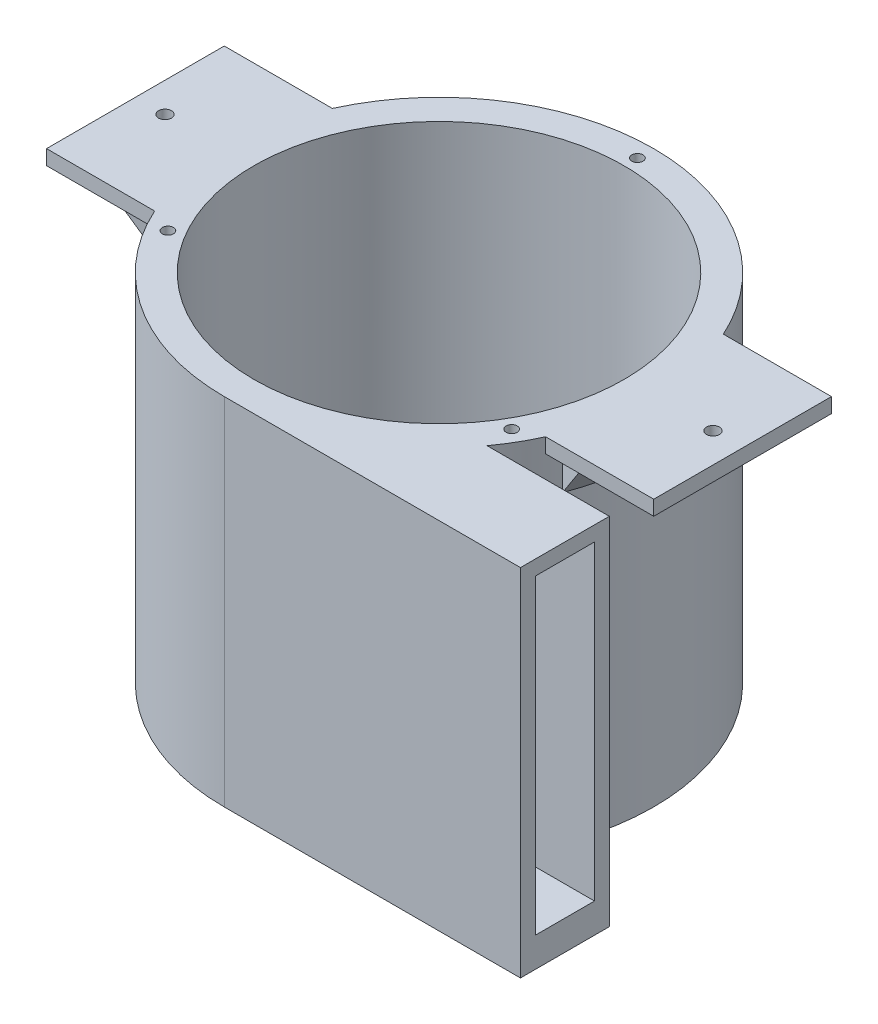
SolidWorks part; units mm, degrees
material "PET"
ref_plane "Front Plane" through (0, 0, 0) normal (0, 0, 1) x (1, 0, 0)
ref_plane "Top Plane" through (0, 0, 0) normal (0, 1, 0) x (1, 0, 0)
ref_plane "Right Plane" through (0, 0, 0) normal (1, 0, 0) x (0, 0, -1)
sketch "Sketch1" plane through (0, 0, 0) normal (0, 1, 0) x (1, 0, 0)
  line L0 (286.7619, 0) -> (-286.7619, 0) construction
  line L1 (0, -187.8106) -> (0, 187.8106) construction
  circle A0 centre (0, 0) radius 90.17 construction
  circle A2 centre (0, 0) radius 92.075
  circle A3 centre (0, 0) radius 79.375
  point P6 (0, 0)
  point P9 (0, 0)
  dimension "D1" = 180.34
  dimension "D3" = 184.15
  dimension "D2" = 12.7
extrude "Boss-Extrude1" add sketch "Sketch1" along normal mid plane 139.7
sketch "Sketch2" plane through (0, -69.85, 0) normal (0, -1, 0) x (1, 0, 0)
  circle A0 centre (0, 0) radius 92.075
extrude "Boss-Extrude2" add sketch "Sketch2" along normal blind 12.7
sketch "Sketch3" plane through (0, -82.55, 0) normal (0, -1, 0) x (1, 0, 0)
  circle A0 centre (0, 0) radius 8.7312
  dimension "D1" = 17.4625
extrude "Cut-Extrude1" cut sketch "Sketch3" against normal blind 12.7
sketch "Sketch4" plane through (0, 69.85, 0) normal (0, 1, 0) x (1, 0, 0)
  line L0 (-164.275, 0) -> (164.275, 0) construction
  line L1 (0, -105.3547) -> (0, 105.3547) construction
  circle A0 centre (0, 0) radius 85.09 construction
  circle A1 centre (0, 85.09) radius 2.3812
  circle A2 centre (73.6901, -42.545) radius 2.3813
  circle A3 centre (-73.6901, -42.545) radius 2.3813
  point P5 (0, 0)
  point P9 (0, 0)
  point P19 (0, 0)
  dimension "D1" = 170.18
  dimension "D2" = 4.7625
  dimension "D3" = 3
extrude "Cut-Extrude2" cut sketch "Sketch4" against normal blind 19.05
sketch "Sketch6" plane through (0, -82.55, 0) normal (0, -1, 0) x (1, 0, 0)
  line L0 (-180.9489, 0) -> (180.9489, 0) construction
  line L1 (0, -132.0673) -> (0, 132.0673) construction
  line L2 (0, 92.075) -> (127, 92.075)
  line L3 (127, 92.075) -> (127, 53.975)
  line L4 (127, 53.975) -> (74.5956, 53.975)
  circle A0 centre (0, 0) radius 92.075 construction
  arc A1 (74.5956, 53.975) -> (0, 92.075) centre (0, 0) ccw
  point P5 (0, 0)
  point P9 (0, 0)
  circle M4 centre (0, 0) radius 92.075
extrude "Boss-Extrude3" add sketch "Sketch6" against normal blind 12.7 contours L4 L3 L2 M4
sketch "Sketch7" plane through (0, 69.85, 0) normal (0, 1, 0) x (1, 0, 0)
  line L0 (0, 133.8457) -> (0, -133.8457) construction
  line L1 (127.6612, 0) -> (-127.6612, 0) construction
  line L2 (0, -92.075) -> (127, -92.075)
  line L3 (0, -92.075) -> (127, -92.075) construction
  line L4 (127, -92.075) -> (127, -53.975)
  line L5 (127, -92.075) -> (127, -53.975) construction
  line L6 (127, -53.975) -> (0, -53.975)
  line L8 (0, -53.975) -> (0, -92.075)
  arc A0 (0, -92.075) -> (74.5956, -53.975) centre (0, 0) ccw construction
  circle A2 centre (0, 0) radius 92.075 construction
  point P5 (0, 0)
  point P9 (0, 0)
  circle M4 centre (0, 0) radius 92.075
  circle M5 centre (0, 0) radius 79.375
extrude "Cut-Extrude4" cut sketch "Sketch7" against normal blind 139.7 contours L4 L6 L2 M4 | L8 L6 M5 M4 | L6 L8 M5
sketch "Sketch8" plane through (0, -69.85, 0) normal (0, 1, 0) x (1, 0, 0)
  line L0 (0, -92.075) -> (127, -92.075)
  line L1 (0, -92.075) -> (127, -92.075) construction
  line L2 (127, -92.075) -> (127, -85.725)
  line L3 (127, -92.075) -> (127, -53.975) construction
  line L6 (0, -79.375) -> (0, -92.075) construction
  line L7 (0, -79.375) -> (0, -92.075) construction
  line L8 (127, -85.725) -> (0, -85.725)
  line L9 (0, -85.725) -> (0, -92.075)
  arc A2 (74.5956, -53.975) -> (0, -92.075) centre (0, 0) ccw construction
  line M4 (0, -79.375) -> (0, -92.075)
  line M5 (0, -92.075) -> (127, -92.075)
  line M6 (127, -92.075) -> (127, -53.975)
extrude "Boss-Extrude4" add sketch "Sketch8" along normal blind 139.7 contours L8 M6 M4 M5
sketch "Sketch9" plane through (0, -69.85, 0) normal (0, 1, 0) x (1, 0, 0)
  line L0 (-187.5492, 0) -> (187.5492, 0) construction
  line L1 (0, 118.5749) -> (0, -118.5749) construction
  line L2 (127, -53.975) -> (58.1987, -53.975)
  line L3 (74.5956, -53.975) -> (58.1987, -53.975) construction
  line L4 (127, -53.975) -> (127, -60.325)
  line L5 (127, -85.725) -> (127, -53.975) construction
  line L6 (127, -60.325) -> (51.5876, -60.325)
  arc A0 (58.1987, -53.975) -> (0, -79.375) centre (0, 0) ccw construction
  arc A1 (58.1987, -53.975) -> (51.5876, -60.325) centre (0, 0) cw
  point P5 (0, 0)
  point P9 (0, 0)
extrude "Boss-Extrude5" add sketch "Sketch9" along normal blind 139.7
sketch "Sketch10" plane through (0, 69.85, 0) normal (0, 1, 0) x (1, 0, 0)
  line L0 (-185.4692, 0) -> (185.4692, 0) construction
  line L1 (0, 111.1683) -> (0, -111.1683) construction
  line L2 (127, -60.325) -> (127, -85.725)
  line L3 (127, -85.725) -> (0, -85.725) construction
  line L4 (127, -92.075) -> (127, -85.725) construction
  line L5 (0, -79.375) -> (0, -85.725)
  line L7 (51.5876, -60.325) -> (127, -60.325) construction
  line L8 (51.5876, -60.325) -> (127, -60.325)
  line L9 (127, -85.725) -> (0, -85.725) construction
  line L10 (0, -85.725) -> (127, -85.725)
  arc A1 (0, -79.375) -> (51.5876, -60.325) centre (0, 0) ccw
  point P5 (0, 0)
  point P9 (0, 0)
  line M1 (0, -85.725) -> (0, -79.375)
  line M3 (51.5876, -60.325) -> (127, -60.325)
  line M9 (127, -85.725) -> (0, -85.725)
extrude "Boss-Extrude6" add sketch "Sketch10" against normal blind 6.35 contours A1 L2 M1 M9 M3
sketch "Sketch11" plane through (0, 69.85, 0) normal (0, 1, 0) x (1, 0, 0)
  line L0 (-164.972, 0) -> (164.972, 0) construction
  line L1 (0, 114.1589) -> (0, -114.1589) construction
  line L2 (130.175, -38.1) -> (130.175, 38.1)
  line L3 (92.075, -62.2053) -> (92.075, 62.2053) construction
  line L4 (130.175, 38.1) -> (83.8224, 38.1)
  line L5 (130.175, -38.1) -> (83.8224, -38.1)
  line L6 (-130.175, -38.1) -> (-83.8224, -38.1)
  line L7 (-130.175, -38.1) -> (-130.175, 38.1)
  line L8 (-130.175, 38.1) -> (-83.8224, 38.1)
  arc A1 (74.5956, -53.975) -> (0, -92.075) centre (0, 0) ccw construction
  arc A2 (83.8224, -38.1) -> (83.8224, 38.1) centre (0, 0) ccw
  arc A3 (-83.8224, -38.1) -> (-83.8224, 38.1) centre (0, 0) cw
  point P5 (0, 0)
  point P9 (0, 0)
  point P12 (130.175, 0)
  point P15 (92.075, 0)
  arc M9 (74.5956, -53.975) -> (0, -92.075) centre (0, 0) ccw
  dimension "D1" = 76.2
  dimension "D2" = 38.1
extrude "Boss-Extrude7" add sketch "Sketch11" against normal blind 6.35 contours L8 L7 L6 M9 | L5 L2 L4 M9
sketch "Sketch13" plane through (0, 0, 0) normal (0, 0, 1) x (1, 0, 0)
  line L0 (0, -102.3984) -> (0, 102.3984) construction
  line L1 (198.786, 0) -> (-198.786, 0) construction
  line L2 (92.075, 63.5) -> (92.075, 47.625)
  line L3 (92.075, -82.55) -> (92.075, 63.5) construction
  line L4 (92.075, 63.5) -> (104.775, 63.5)
  line L5 (130.175, 63.5) -> (83.8224, 63.5) construction
  line L6 (104.775, 63.5) -> (92.075, 47.625)
  line L7 (-92.075, 63.5) -> (-92.075, 47.625)
  line L8 (-92.075, 63.5) -> (-104.775, 63.5)
  line L9 (-104.775, 63.5) -> (-92.075, 47.625)
  point P4 (0, 0)
  point P8 (0, 0)
revolve "Revolve1" add sketch "Sketch13" angle 21 about L0 other way angle 21
sketch "Sketch14" plane through (0, 69.85, 0) normal (0, 1, 0) x (1, 0, 0)
  line L0 (-194.107, 0) -> (194.107, 0) construction
  line L1 (0, -131.9221) -> (0, 131.9221) construction
  line L2 (-104.775, -88.2363) -> (-104.775, 88.2363) construction
  circle A0 centre (-117.475, 0) radius 2.7781
  circle A1 centre (117.475, 0) radius 2.7781
  point P5 (0, 0)
  point P9 (0, 0)
  point P12 (-104.775, 0)
  dimension "D2" = 5.5562
  dimension "D3" = 12.7
  dimension "D1" = 104.775
extrude "Cut-Extrude5" cut sketch "Sketch14" against normal blind 9.525
